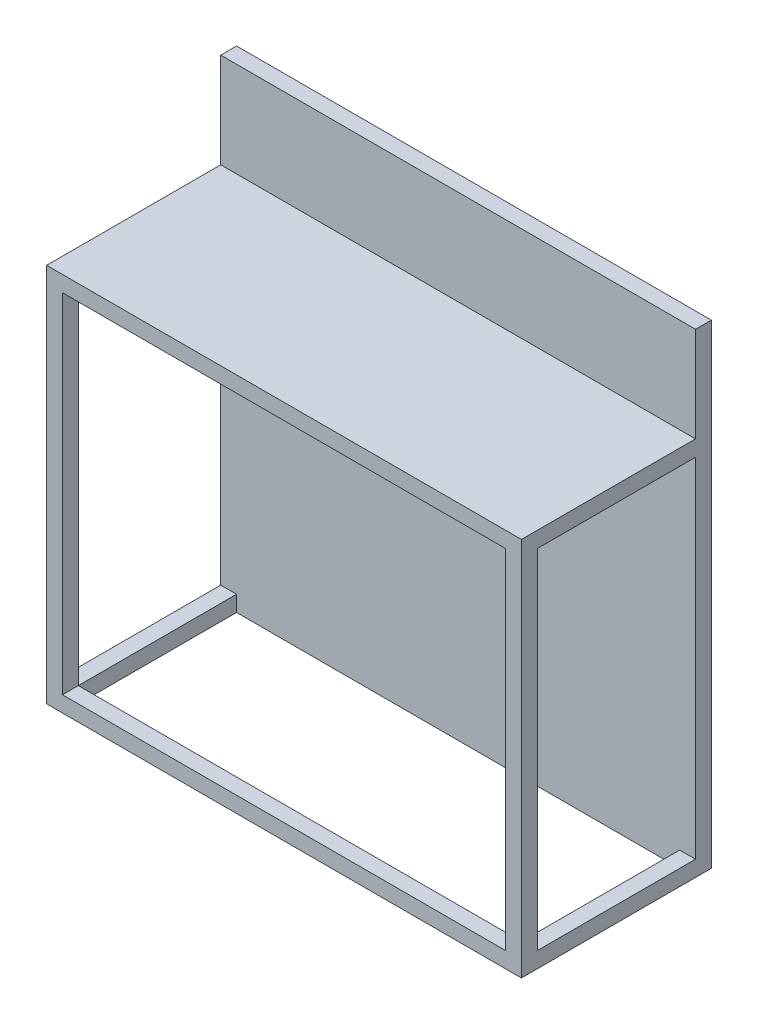
SolidWorks part; units mm, degrees
ref_plane "Front Plane" through (0, 0, 0) normal (0, 0, 1) x (1, 0, 0)
ref_plane "Top Plane" through (0, 0, 0) normal (0, 1, 0) x (1, 0, 0)
ref_plane "Right Plane" through (0, 0, 0) normal (1, 0, 0) x (0, 0, -1)
sketch "Sketch1" plane through (0, 0, 0) normal (0, 0, 1) x (1, 0, 0)
  line L1 (750, -750) -> (-750, -750)
  line L2 (750, -750) -> (750, 750)
  line L3 (750, 750) -> (-750, 750)
  line L4 (-750, -750) -> (-750, 750)
  line L5 (750, -750) -> (-750, 750) construction
  line L6 (750, 750) -> (-750, -750) construction
  point P1 (0, 0)
  dimension "D1" = 1500
  dimension "D2" = 1500
extrude "Boss-Extrude1" add sketch "Sketch1" along normal blind 600
sketch "Sketch4" plane through (-750, 0, 0) normal (-1, 0, 0) x (0, 0, 1)
  line L0 (600, 750) -> (0, 750) construction
  line L1 (50, 750) -> (600, 750)
  line L2 (50, 750) -> (50, 450)
  line L3 (50, 450) -> (600, 450)
  line L4 (600, 750) -> (600, 450)
  line L5 (50, 750) -> (600, 450) construction
  line L6 (50, 450) -> (600, 750) construction
  line L7 (600, 750) -> (600, -750) construction
  line L8 (0, 750) -> (0, -750) construction
  point P4 (325, 600)
  dimension "D1" = 50
  dimension "D2" = 300
extrude "Cut-Extrude1" cut sketch "Sketch4" against normal up to next
sketch "Sketch5" plane through (0, -750, 0) normal (0, -1, 0) x (1, 0, 0)
  line L0 (-750, 600) -> (750, 600) construction
  line L1 (700, 50) -> (-700, 50)
  line L2 (700, 50) -> (700, 550)
  line L3 (700, 550) -> (-700, 550)
  line L4 (-700, 50) -> (-700, 550)
  line L5 (700, 50) -> (-700, 550) construction
  line L6 (700, 550) -> (-700, 50) construction
  line L7 (-750, 600) -> (-750, 0) construction
  line L8 (750, 600) -> (750, 0) construction
  line L9 (-750, 0) -> (750, 0) construction
  point P0 (0, 300)
  dimension "D1" = 50
  dimension "D2" = 50
  dimension "D3" = 50
  dimension "D4" = 50
extrude "Cut-Extrude2" cut sketch "Sketch5" against normal blind 1150
sketch "Sketch6" plane through (-750, 0, 0) normal (-1, 0, 0) x (0, 0, 1)
  line L0 (50, 450) -> (600, 450) construction
  line L1 (50, 400) -> (550, 400)
  line L2 (50, 400) -> (50, -700)
  line L3 (50, -700) -> (550, -700)
  line L4 (550, 400) -> (550, -700)
  line L5 (50, 400) -> (550, -700) construction
  line L6 (50, -700) -> (550, 400) construction
  line L7 (0, 750) -> (0, -750) construction
  line L8 (600, 450) -> (600, -750) construction
  line L9 (600, -750) -> (0, -750) construction
  point P4 (300, -150)
  dimension "D1" = 50
  dimension "D2" = 50
  dimension "D3" = 50
  dimension "D4" = 50
extrude "Cut-Extrude3" cut sketch "Sketch6" against normal blind 2364
sketch "Sketch7" plane through (0, 0, 600) normal (0, 0, 1) x (1, 0, 0)
  line L0 (750, 450) -> (-750, 450) construction
  line L1 (-700, 400) -> (700, 400)
  line L2 (-700, 400) -> (-700, -700)
  line L3 (-700, -700) -> (700, -700)
  line L4 (700, 400) -> (700, -700)
  line L5 (-700, 400) -> (700, -700) construction
  line L6 (-700, -700) -> (700, 400) construction
  line L7 (-750, 450) -> (-750, -750) construction
  line L8 (750, -750) -> (750, 450) construction
  line L9 (-750, -750) -> (750, -750) construction
  point P4 (0, -150)
  dimension "D1" = 50
  dimension "D2" = 50
  dimension "D3" = 50
  dimension "D4" = 50
extrude "Cut-Extrude4" cut sketch "Sketch7" against normal blind 320
